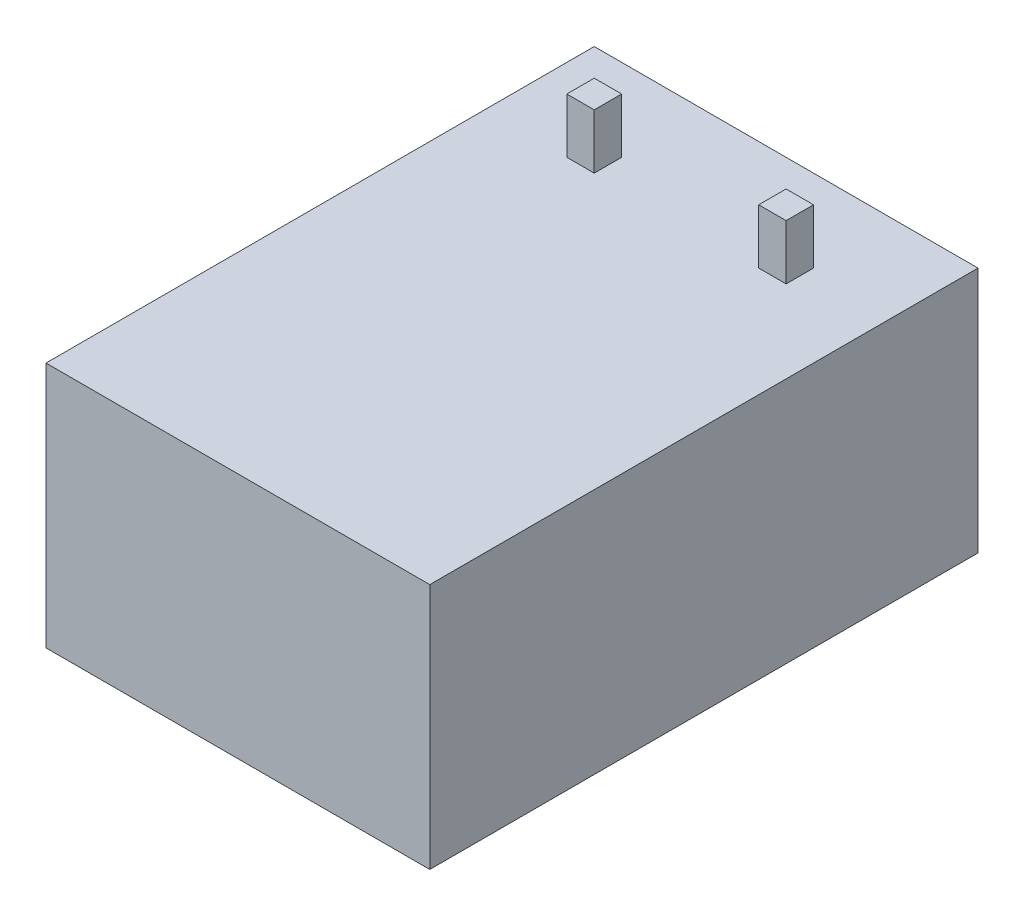
SolidWorks part; units mm, degrees
ref_plane "前视基准面" through (0, 0, 0) normal (0, 0, 1) x (1, 0, 0)
ref_plane "上视基准面" through (0, 0, 0) normal (0, 1, 0) x (1, 0, 0)
ref_plane "右视基准面" through (0, 0, 0) normal (1, 0, 0) x (0, 0, -1)
sketch "草图1" plane through (0, 0, 0) normal (0, 1, 0) x (1, 0, 0)
  line L1 (-35, 50) -> (35, 50)
  line L2 (-35, 50) -> (-35, -50)
  line L3 (-35, -50) -> (35, -50)
  line L4 (35, 50) -> (35, -50)
  line L5 (0, -50) -> (0, 50) construction
  line L6 (-35, 0) -> (35, 0) construction
  point P0 (0, 0)
  dimension "D1" = 70
  dimension "D2" = 100
extrude "凸台-拉伸1" add sketch "草图1" along normal blind 45
sketch "草图2" plane through (0, 45, 0) normal (0, 1, 0) x (1, 0, 0)
  line L0 (0, 50) -> (0, -50) construction
  line L1 (15, 35) -> (20, 35)
  line L2 (15, 35) -> (15, 30)
  line L3 (15, 30) -> (20, 30)
  line L4 (20, 35) -> (20, 30)
  line L5 (-20, 35) -> (-15, 35)
  line L6 (-20, 35) -> (-20, 30)
  line L7 (-20, 30) -> (-15, 30)
  line L8 (-15, 35) -> (-15, 30)
  line L9 (35, 50) -> (-35, 50) construction
  line L10 (-35, -50) -> (35, -50) construction
  point P14 (-15, 32.5)
  dimension "D1" = 5
  dimension "D2" = 5
  dimension "D3" = 5
  dimension "D4" = 5
  dimension "D5" = 30
  dimension "D6" = 15
extrude "凸台-拉伸2" add sketch "草图2" along normal blind 10
